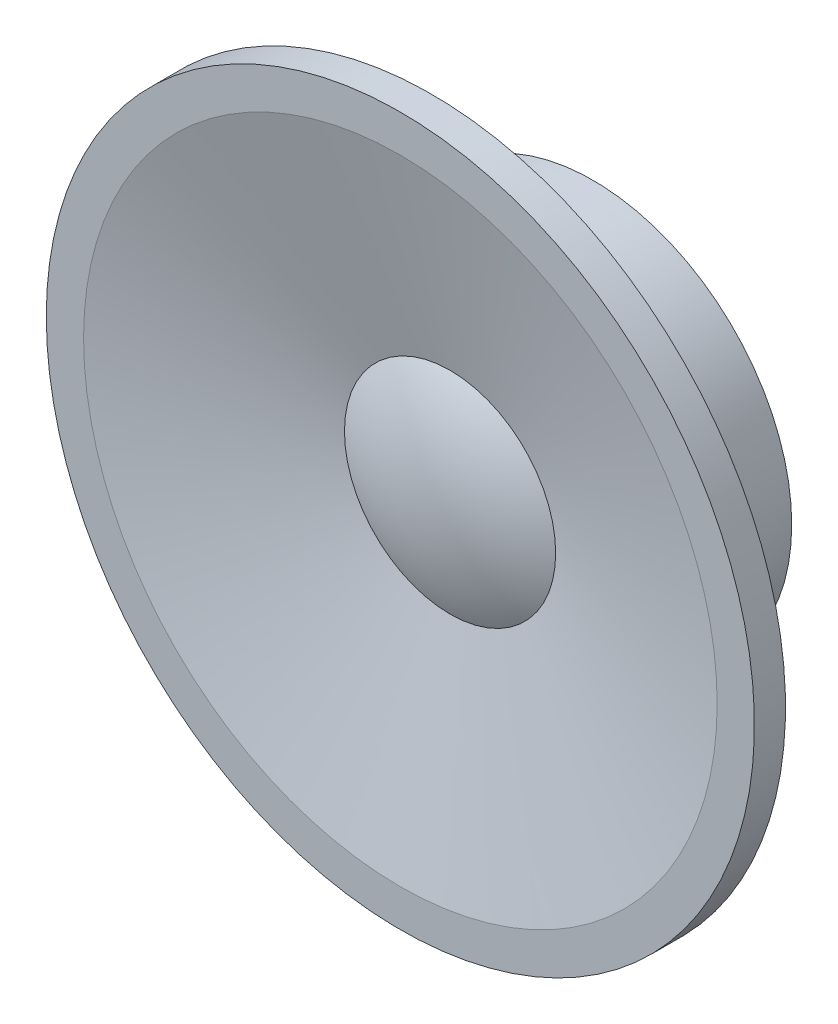
SolidWorks part; units mm, degrees
ref_plane "Front Plane" through (0, 0, 0) normal (0, 0, 1) x (1, 0, 0)
ref_plane "Top Plane" through (0, 0, 0) normal (0, 1, 0) x (1, 0, 0)
ref_plane "Right Plane" through (0, 0, 0) normal (1, 0, 0) x (0, 0, -1)
sketch "Sketch2" plane through (0, 0, 0) normal (0, 1, 0) x (1, 0, 0)
  line L0 (0, 0) -> (25.5, 0) construction
  line L1 (25.5, 0) -> (28.5, 0)
  line L2 (28.5, 0) -> (28.5, 2.5)
  line L3 (28.5, 2.5) -> (26.5, 2.5)
  line L4 (26.5, 2.5) -> (16, 7.5)
  line L5 (16, 7.5) -> (16, 15.5)
  line L6 (16, 15.5) -> (14, 15.5)
  line L7 (14, 15.5) -> (14, 16.5)
  line L8 (14, 16.5) -> (0, 16.5)
  line L9 (8.5, 4) -> (25.5, 0)
  line L10 (0, 16.5) -> (0, 2)
  arc A0 (0, 2) -> (8.5, 4) centre (0, 21.0625) ccw
  point P14 (0, 0)
  point P15 (0, 2.2442)
  point P16 (8.5, 5.6959)
  point P17 (26.4497, 2.5)
  point P18 (26.5697, 2)
  dimension "D1" = 16
  dimension "D2" = 1
  dimension "D3" = 2
  dimension "D4" = 16.5
  dimension "D5" = 9
  dimension "D6" = 3
  dimension "D7" = 28.5
  dimension "D8" = 8.5
  dimension "D9" = 2
  dimension "D10" = 4
  dimension "D11" = 2.5
  dimension "D12" = 2
revolve "Revolve1" add sketch "Sketch2" angle 360 about L10
